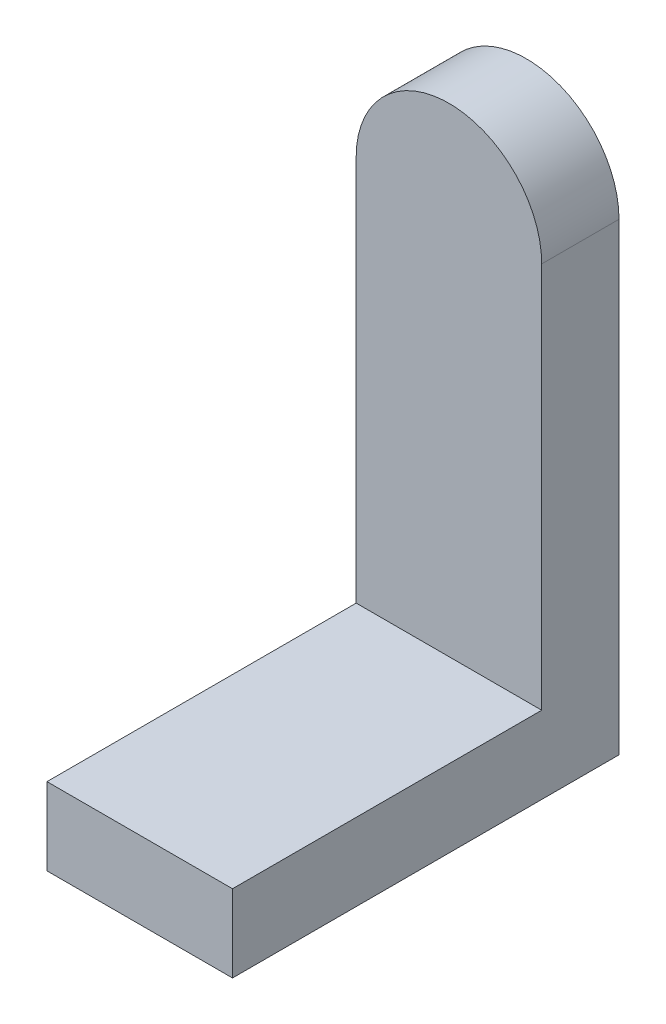
SolidWorks part; units mm, degrees
ref_plane "Front Plane" through (0, 0, 0) normal (0, 0, 1) x (1, 0, 0)
ref_plane "Top Plane" through (0, 0, 0) normal (0, 1, 0) x (1, 0, 0)
ref_plane "Right Plane" through (0, 0, 0) normal (1, 0, 0) x (0, 0, -1)
sketch "Sketch1" plane through (0, 0, 0) normal (0, 0, 1) x (1, 0, 0)
  line L1 (-6, 15) -> (6, 15)
  line L2 (-6, 15) -> (-6, -15)
  line L3 (-6, -15) -> (6, -15)
  line L4 (6, 15) -> (6, -15)
  line L5 (-6, 15) -> (6, -15) construction
  line L6 (-6, -15) -> (6, 15) construction
  circle A0 centre (0, 15) radius 6
  point P0 (0, 0)
  dimension "D1" = 12
  dimension "D2" = 30
extrude "Boss-Extrude1" add sketch "Sketch1" along normal blind 5 contours L1 A0 | L1 A0 | A0 L2 L3 L4
sketch "Sketch2" plane through (6, 0, 0) normal (1, 0, 0) x (0, 0, -1)
  line L1 (-5, -15) -> (-25, -15)
  line L2 (-5, -15) -> (-5, -10)
  line L3 (-5, -10) -> (-25, -10)
  line L4 (-25, -15) -> (-25, -10)
  dimension "D1" = 20
  dimension "D2" = 5
extrude "Boss-Extrude2" add sketch "Sketch2" against normal blind 12
